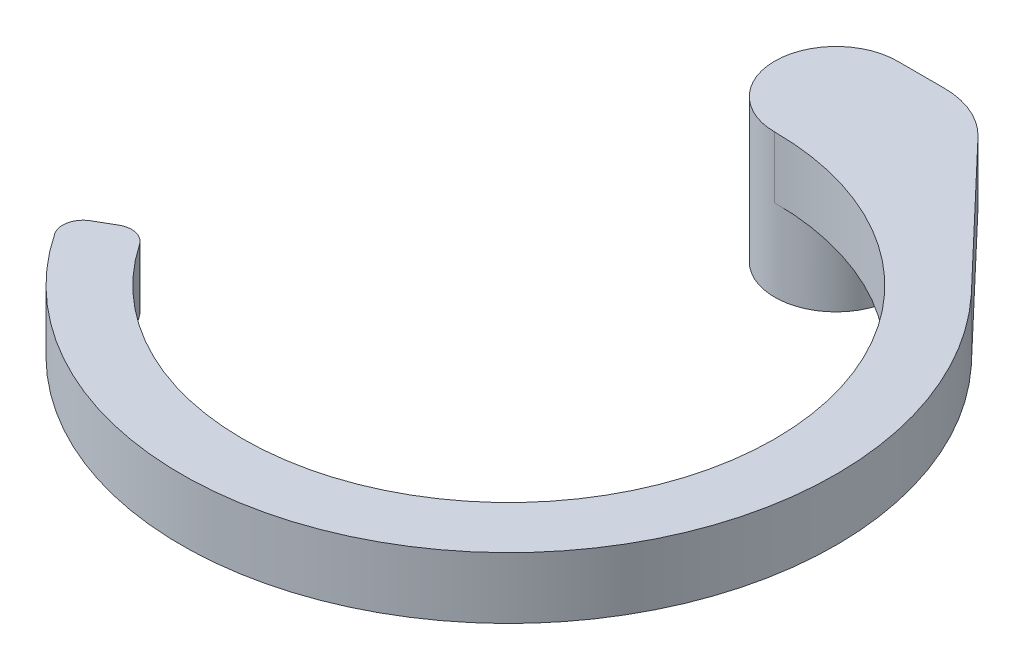
SolidWorks part; units mm, degrees
ref_plane "正面" through (0, 0, 0) normal (0, 0, 1) x (1, 0, 0)
ref_plane "平面" through (0, 0, 0) normal (0, 1, 0) x (1, 0, 0)
ref_plane "右側面" through (0, 0, 0) normal (1, 0, 0) x (0, 0, -1)
sketch "ｽｹｯﾁ2" plane through (0, 0, 0) normal (0, 1, 0) x (1, 0, 0)
  line L1 (-1.8089, 2.6033) -> (0, 0)
  line L2 (-60.4669, -34.9106) -> (-64.8074, -37.4166)
  line L4 (0, 95) -> (11.4274, 95)
  line L5 (25.9115, 88.7917) -> (58.5757, 54.4875)
  arc A0 (-66.4612, -44.5298) -> (57.2894, 55.8384) centre (0, 0) ccw
  arc A1 (-53.8264, -36.4378) -> (0, 65) centre (0, 0) ccw
  arc A2 (0, 95) -> (0, 65) centre (0, 80) ccw
  arc A3 (11.4274, 95) -> (25.9115, 88.7917) centre (11.4274, 75) cw
  arc A4 (-53.8264, -36.4378) -> (-60.4669, -34.9106) centre (-57.9669, -39.2407) ccw
  arc A5 (-66.4612, -44.5298) -> (-64.8074, -37.4166) centre (-62.3074, -41.7467) cw
  dimension "D1" = 160
  dimension "D2" = 130
  dimension "D4" = 20
  dimension "D5" = 5
  dimension "D6" = 5
extrude "ﾎﾞｽ - 押し出し4" add sketch "ｽｹｯﾁ2" along normal blind 15 contours A5 A0 L5 A3 L4 A2 A1 A4 L2
sketch "ｽｹｯﾁ4" plane through (0, 0, 0) normal (0, -1, 0) x (1, 0, 0)
  circle A0 centre (0, -80) radius 15
  dimension "D1" = 30
extrude "ﾎﾞｽ - 押し出し5" add sketch "ｽｹｯﾁ4" along normal blind 20
sketch "ｽｹｯﾁ5" plane through (0, -20, 0) normal (0, -1, 0) x (-1, 0, 0)
  circle A0 centre (0, 80) radius 10.1
  dimension "D1" = 20.2
extrude "ｶｯﾄ - 押し出し1" cut sketch "ｽｹｯﾁ5" against normal blind 2
